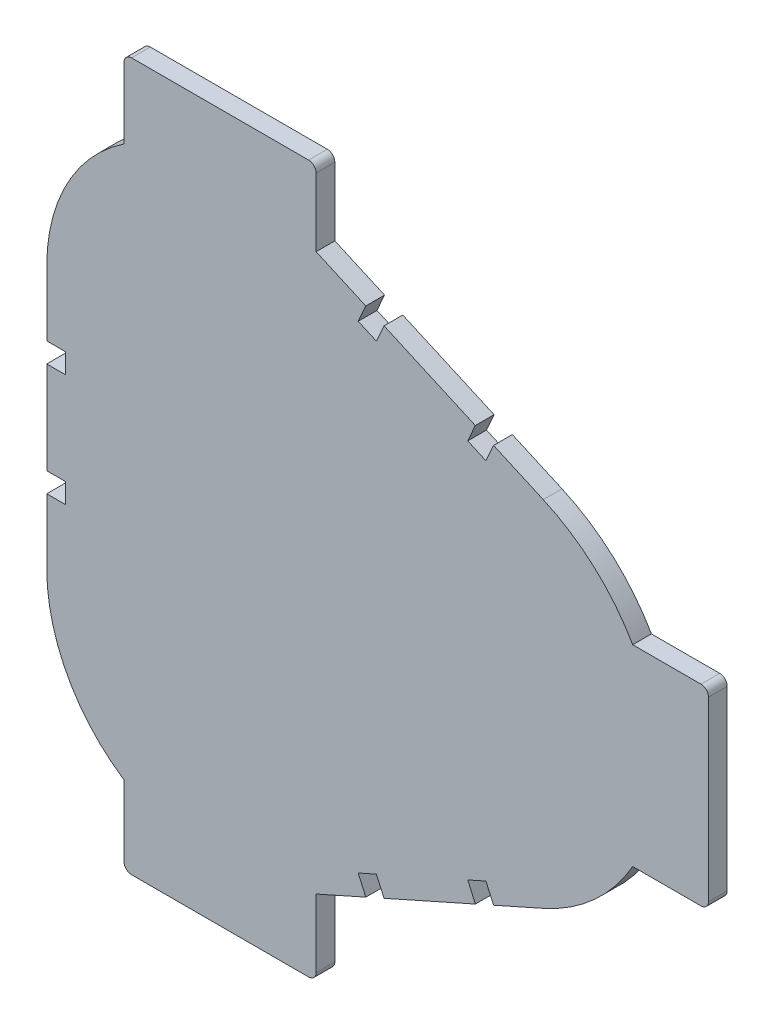
SolidWorks part; units mm, degrees
ref_plane "Front Plane" through (0, 0, 0) normal (0, 0, 1) x (1, 0, 0)
ref_plane "Top Plane" through (0, 0, 0) normal (0, 1, 0) x (1, 0, 0)
ref_plane "Right Plane" through (0, 0, 0) normal (1, 0, 0) x (0, 0, -1)
sketch "Sketch1" plane through (0, 0, -130.81) normal (0, 0, -1) x (-1, 0, 0)
  line L0 (70.5268, 62.4132) -> (70.5268, 49.4592) construction
  line L1 (70.5268, 49.4592) -> (76.8768, 49.4592) construction
  line L2 (76.8768, 49.4592) -> (76.8768, 62.4132) construction
  line L3 (76.8768, 62.4132) -> (70.5268, 62.4132) construction
  line L4 (70.5268, 24.3132) -> (70.5268, 11.3592) construction
  line L5 (70.5268, 11.3592) -> (76.8768, 11.3592) construction
  line L6 (76.8768, 11.3592) -> (76.8768, 24.3132) construction
  line L7 (76.8768, 24.3132) -> (70.5268, 24.3132) construction
  line L8 (76.8768, 52.558) -> (70.5268, 52.558) construction
  line L9 (70.5268, 52.558) -> (70.5268, 21.2144) construction
  line L10 (70.5268, 21.2144) -> (76.8768, 21.2144) construction
  line L11 (76.8768, 21.2144) -> (76.8768, 52.558) construction
  line L12 (-8.0545, -76.637) -> (-8.0545, -54.8958) construction
  line L13 (-9.5612, -52.5755) -> (-28.6575, -44.0718) construction
  line L14 (-28.6575, -44.0718) -> (-31.2406, -49.8726) construction
  line L15 (-31.2406, -49.8726) -> (-14.4045, -57.3699) construction
  line L16 (-14.4045, -57.3699) -> (-14.4045, -80.447) construction
  line L17 (-11.8645, -82.987) -> (48.143, -82.987) construction
  line L18 (50.683, -80.447) -> (50.683, -56.4617) construction
  line L19 (76.8768, -7.5638) -> (76.8768, 14.458) construction
  line L20 (76.8768, 14.458) -> (70.5268, 14.458) construction
  line L21 (70.5268, 14.458) -> (70.5268, -7.5638) construction
  line L22 (44.333, -54.3762) -> (44.333, -76.637) construction
  line L23 (44.333, -76.637) -> (-8.0545, -76.637) construction
  line L24 (-37.6604, -40.0627) -> (-40.2435, -45.8635) construction
  line L25 (-40.2435, -45.8635) -> (-28.4098, -51.1332) construction
  line L26 (-28.4098, -51.1332) -> (-25.8267, -45.3323) construction
  line L27 (-25.8267, -45.3323) -> (-37.6604, -40.0627) construction
  line L28 (-74.7857, -23.5304) -> (-77.3689, -29.3312) construction
  line L29 (-77.3689, -29.3312) -> (-65.5352, -34.6009) construction
  line L30 (-65.5352, -34.6009) -> (-62.952, -28.8001) construction
  line L31 (-62.952, -28.8001) -> (-74.7857, -23.5304) construction
  line L32 (-34.8296, -41.3233) -> (-65.7828, -27.5395) construction
  line L33 (-65.7828, -27.5395) -> (-68.366, -33.3403) construction
  line L34 (-68.366, -33.3403) -> (-37.4127, -47.1241) construction
  line L35 (-37.4127, -47.1241) -> (-34.8296, -41.3233) construction
  line L36 (-121.6907, 69.4299) -> (-144.8373, 69.4299) construction
  line L37 (-147.3773, 66.8899) -> (-147.3773, 6.8824) construction
  line L38 (-144.8373, 4.3424) -> (-121.6907, 4.3424) construction
  line L39 (-91.3743, -23.0945) -> (-74.5381, -30.5918) construction
  line L40 (-74.5381, -30.5918) -> (-71.9549, -24.791) construction
  line L41 (-71.9549, -24.791) -> (-88.7911, -17.2937) construction
  line L42 (-119.4336, 10.6924) -> (-138.4873, 10.6924) construction
  line L43 (-141.0273, 13.2324) -> (-141.0273, 60.5399) construction
  line L44 (-138.4873, 63.0799) -> (-119.4336, 63.0799) construction
  line L45 (-88.7911, 91.066) -> (-71.9549, 98.5633) construction
  line L46 (-71.9549, 98.5633) -> (-74.5381, 104.3642) construction
  line L47 (-74.5381, 104.3642) -> (-91.3743, 96.8669) construction
  line L48 (-74.7857, 97.3027) -> (-62.952, 102.5724) construction
  line L49 (-62.952, 102.5724) -> (-65.5352, 108.3732) construction
  line L50 (-65.5352, 108.3732) -> (-77.3689, 103.1036) construction
  line L51 (-77.3689, 103.1036) -> (-74.7857, 97.3027) construction
  line L52 (-68.366, 107.1127) -> (-65.7828, 101.3118) construction
  line L53 (-65.7828, 101.3118) -> (-34.8296, 115.0956) construction
  line L54 (-34.8296, 115.0956) -> (-37.4127, 120.8965) construction
  line L55 (-37.4127, 120.8965) -> (-68.366, 107.1127) construction
  line L56 (-37.6604, 113.835) -> (-25.8267, 119.1047) construction
  line L57 (-25.8267, 119.1047) -> (-28.4098, 124.9055) construction
  line L58 (-28.4098, 124.9055) -> (-40.2435, 119.6359) construction
  line L59 (-40.2435, 119.6359) -> (-37.6604, 113.835) construction
  line L60 (-28.6575, 117.8441) -> (-9.5612, 126.3479) construction
  line L61 (-8.0545, 128.6682) -> (-8.0545, 147.8693) construction
  line L62 (-5.5145, 150.4093) -> (41.793, 150.4093) construction
  line L63 (44.333, 147.8693) -> (44.333, 128.1486) construction
  line L64 (70.5268, 81.3362) -> (70.5268, 59.3144) construction
  line L65 (70.5268, 59.3144) -> (76.8768, 59.3144) construction
  line L66 (76.8768, 59.3144) -> (76.8768, 81.3362) construction
  line L67 (50.683, 130.234) -> (50.683, 154.2193) construction
  line L68 (48.143, 156.7593) -> (-11.8645, 156.7593) construction
  line L69 (-14.4045, 154.2193) -> (-14.4045, 131.1423) construction
  line L70 (-14.4045, 131.1423) -> (-31.2406, 123.6449) construction
  line L71 (-31.2406, 123.6449) -> (-28.6575, 117.8441) construction
  line L72 (70.5268, 62.4132) -> (70.5268, 49.4592)
  line L73 (70.5268, 49.4592) -> (76.8768, 49.4592)
  line L74 (76.8768, 49.4592) -> (76.8768, 62.4132)
  line L75 (76.8768, 62.4132) -> (70.5268, 62.4132)
  line L76 (70.5268, 24.3132) -> (70.5268, 11.3592)
  line L77 (70.5268, 11.3592) -> (76.8768, 11.3592)
  line L78 (76.8768, 11.3592) -> (76.8768, 24.3132)
  line L79 (76.8768, 24.3132) -> (70.5268, 24.3132)
  line L80 (76.8768, 52.558) -> (70.5268, 52.558)
  line L81 (70.5268, 52.558) -> (70.5268, 21.2144)
  line L82 (70.5268, 21.2144) -> (76.8768, 21.2144)
  line L83 (76.8768, 21.2144) -> (76.8768, 52.558)
  line L84 (-8.0545, -76.637) -> (-8.0545, -54.8958)
  line L85 (-9.5612, -52.5755) -> (-28.6575, -44.0718)
  line L86 (-28.6575, -44.0718) -> (-31.2406, -49.8726)
  line L87 (-31.2406, -49.8726) -> (-14.4045, -57.3699)
  line L88 (-14.4045, -57.3699) -> (-14.4045, -80.447)
  line L89 (-11.8645, -82.987) -> (48.143, -82.987)
  line L90 (50.683, -80.447) -> (50.683, -56.4617)
  line L91 (76.8768, -7.5638) -> (76.8768, 14.458)
  line L92 (76.8768, 14.458) -> (70.5268, 14.458)
  line L93 (70.5268, 14.458) -> (70.5268, -7.5638)
  line L94 (44.333, -54.3762) -> (44.333, -76.637)
  line L95 (44.333, -76.637) -> (-8.0545, -76.637)
  line L96 (-37.6604, -40.0627) -> (-40.2435, -45.8635)
  line L97 (-40.2435, -45.8635) -> (-28.4098, -51.1332)
  line L98 (-28.4098, -51.1332) -> (-25.8267, -45.3323)
  line L99 (-25.8267, -45.3323) -> (-37.6604, -40.0627)
  line L100 (-74.7857, -23.5304) -> (-77.3689, -29.3312)
  line L101 (-77.3689, -29.3312) -> (-65.5352, -34.6009)
  line L102 (-65.5352, -34.6009) -> (-62.952, -28.8001)
  line L103 (-62.952, -28.8001) -> (-74.7857, -23.5304)
  line L104 (-34.8296, -41.3233) -> (-65.7828, -27.5395)
  line L105 (-65.7828, -27.5395) -> (-68.366, -33.3403)
  line L106 (-68.366, -33.3403) -> (-37.4127, -47.1241)
  line L107 (-37.4127, -47.1241) -> (-34.8296, -41.3233)
  line L108 (-121.6907, 69.4299) -> (-144.8373, 69.4299)
  line L109 (-147.3773, 66.8899) -> (-147.3773, 6.8824)
  line L110 (-144.8373, 4.3424) -> (-121.6907, 4.3424)
  line L111 (-91.3743, -23.0945) -> (-74.5381, -30.5918)
  line L112 (-74.5381, -30.5918) -> (-71.9549, -24.791)
  line L113 (-71.9549, -24.791) -> (-88.7911, -17.2937)
  line L114 (-119.4336, 10.6924) -> (-138.4873, 10.6924)
  line L115 (-141.0273, 13.2324) -> (-141.0273, 60.5399)
  line L116 (-138.4873, 63.0799) -> (-119.4336, 63.0799)
  line L117 (-88.7911, 91.066) -> (-71.9549, 98.5633)
  line L118 (-71.9549, 98.5633) -> (-74.5381, 104.3642)
  line L119 (-74.5381, 104.3642) -> (-91.3743, 96.8669)
  line L120 (-74.7857, 97.3027) -> (-62.952, 102.5724)
  line L121 (-62.952, 102.5724) -> (-65.5352, 108.3732)
  line L122 (-65.5352, 108.3732) -> (-77.3689, 103.1036)
  line L123 (-77.3689, 103.1036) -> (-74.7857, 97.3027)
  line L124 (-68.366, 107.1127) -> (-65.7828, 101.3118)
  line L125 (-65.7828, 101.3118) -> (-34.8296, 115.0956)
  line L126 (-34.8296, 115.0956) -> (-37.4127, 120.8965)
  line L127 (-37.4127, 120.8965) -> (-68.366, 107.1127)
  line L128 (-37.6604, 113.835) -> (-25.8267, 119.1047)
  line L129 (-25.8267, 119.1047) -> (-28.4098, 124.9055)
  line L130 (-28.4098, 124.9055) -> (-40.2435, 119.6359)
  line L131 (-40.2435, 119.6359) -> (-37.6604, 113.835)
  line L132 (-28.6575, 117.8441) -> (-9.5612, 126.3479)
  line L133 (-8.0545, 128.6682) -> (-8.0545, 147.8693)
  line L134 (-5.5145, 150.4093) -> (41.793, 150.4093)
  line L135 (44.333, 147.8693) -> (44.333, 128.1486)
  line L136 (70.5268, 81.3362) -> (70.5268, 59.3144)
  line L137 (70.5268, 59.3144) -> (76.8768, 59.3144)
  line L138 (76.8768, 59.3144) -> (76.8768, 81.3362)
  line L139 (50.683, 130.234) -> (50.683, 154.2193)
  line L140 (48.143, 156.7593) -> (-11.8645, 156.7593)
  line L141 (-14.4045, 154.2193) -> (-14.4045, 131.1423)
  line L142 (-14.4045, 131.1423) -> (-31.2406, 123.6449)
  line L143 (-31.2406, 123.6449) -> (-28.6575, 117.8441)
  arc A0 (-8.0545, -54.8958) -> (-9.5612, -52.5755) centre (-10.5945, -54.8958) ccw construction
  arc A1 (-14.4045, -80.447) -> (-11.8645, -82.987) centre (-11.8645, -80.447) ccw construction
  arc A2 (48.143, -82.987) -> (50.683, -80.447) centre (48.143, -80.447) ccw construction
  arc A3 (50.683, -56.4617) -> (76.8768, -7.5638) centre (18.1393, -7.5638) ccw construction
  arc A4 (45.5443, -52.2115) -> (70.5268, -7.5638) centre (18.1393, -7.5638) ccw construction
  arc A5 (45.5443, -52.2115) -> (44.333, -54.3762) centre (46.873, -54.3762) ccw construction
  arc A6 (-144.8373, 69.4299) -> (-147.3773, 66.8899) centre (-144.8373, 66.8899) ccw construction
  arc A7 (-147.3773, 6.8824) -> (-144.8373, 4.3424) centre (-144.8373, 6.8824) ccw construction
  arc A8 (-121.6907, 4.3424) -> (-91.3743, -23.0945) centre (-64.6643, 36.8862) ccw construction
  arc A9 (-117.1843, 9.3325) -> (-88.7911, -17.2937) centre (-64.6643, 36.8862) ccw construction
  arc A10 (-117.1843, 9.3325) -> (-119.4336, 10.6924) centre (-119.4336, 8.1524) ccw construction
  arc A11 (-141.0273, 13.2324) -> (-138.4873, 10.6924) centre (-138.4873, 13.2324) ccw construction
  arc A12 (-138.4873, 63.0799) -> (-141.0273, 60.5399) centre (-138.4873, 60.5399) ccw construction
  arc A13 (-119.4336, 63.0799) -> (-117.1843, 64.4399) centre (-119.4336, 65.6199) ccw construction
  arc A14 (-88.7911, 91.066) -> (-117.1843, 64.4399) centre (-64.6643, 36.8862) ccw construction
  arc A15 (-91.3743, 96.8669) -> (-121.6907, 69.4299) centre (-64.6643, 36.8862) ccw construction
  arc A16 (-9.5612, 126.3479) -> (-8.0545, 128.6682) centre (-10.5945, 128.6682) ccw construction
  arc A17 (-5.5145, 150.4093) -> (-8.0545, 147.8693) centre (-5.5145, 147.8693) ccw construction
  arc A18 (44.333, 147.8693) -> (41.793, 150.4093) centre (41.793, 147.8693) ccw construction
  arc A19 (44.333, 128.1486) -> (45.5443, 125.9839) centre (46.873, 128.1486) ccw construction
  arc A20 (70.5268, 81.3362) -> (45.5443, 125.9839) centre (18.1393, 81.3362) ccw construction
  arc A21 (76.8768, 81.3362) -> (50.683, 130.234) centre (18.1393, 81.3362) ccw construction
  arc A22 (50.683, 154.2193) -> (48.143, 156.7593) centre (48.143, 154.2193) ccw construction
  arc A23 (-11.8645, 156.7593) -> (-14.4045, 154.2193) centre (-11.8645, 154.2193) ccw construction
  arc A24 (-8.0545, -54.8958) -> (-9.5612, -52.5755) centre (-10.5945, -54.8958) ccw
  arc A25 (-14.4045, -80.447) -> (-11.8645, -82.987) centre (-11.8645, -80.447) ccw
  arc A26 (48.143, -82.987) -> (50.683, -80.447) centre (48.143, -80.447) ccw
  arc A27 (50.683, -56.4617) -> (76.8768, -7.5638) centre (18.1393, -7.5638) ccw
  arc A28 (45.5443, -52.2115) -> (70.5268, -7.5638) centre (18.1393, -7.5638) ccw
  arc A29 (45.5443, -52.2115) -> (44.333, -54.3762) centre (46.873, -54.3762) ccw
  arc A30 (-144.8373, 69.4299) -> (-147.3773, 66.8899) centre (-144.8373, 66.8899) ccw
  arc A31 (-147.3773, 6.8824) -> (-144.8373, 4.3424) centre (-144.8373, 6.8824) ccw
  arc A32 (-121.6907, 4.3424) -> (-91.3743, -23.0945) centre (-64.6643, 36.8862) ccw
  arc A33 (-117.1843, 9.3325) -> (-88.7911, -17.2937) centre (-64.6643, 36.8862) ccw
  arc A34 (-117.1843, 9.3325) -> (-119.4336, 10.6924) centre (-119.4336, 8.1524) ccw
  arc A35 (-141.0273, 13.2324) -> (-138.4873, 10.6924) centre (-138.4873, 13.2324) ccw
  arc A36 (-138.4873, 63.0799) -> (-141.0273, 60.5399) centre (-138.4873, 60.5399) ccw
  arc A37 (-119.4336, 63.0799) -> (-117.1843, 64.4399) centre (-119.4336, 65.6199) ccw
  arc A38 (-88.7911, 91.066) -> (-117.1843, 64.4399) centre (-64.6643, 36.8862) ccw
  arc A39 (-91.3743, 96.8669) -> (-121.6907, 69.4299) centre (-64.6643, 36.8862) ccw
  arc A40 (-9.5612, 126.3479) -> (-8.0545, 128.6682) centre (-10.5945, 128.6682) ccw
  arc A41 (-5.5145, 150.4093) -> (-8.0545, 147.8693) centre (-5.5145, 147.8693) ccw
  arc A42 (44.333, 147.8693) -> (41.793, 150.4093) centre (41.793, 147.8693) ccw
  arc A43 (44.333, 128.1486) -> (45.5443, 125.9839) centre (46.873, 128.1486) ccw
  arc A44 (70.5268, 81.3362) -> (45.5443, 125.9839) centre (18.1393, 81.3362) ccw
  arc A45 (76.8768, 81.3362) -> (50.683, 130.234) centre (18.1393, 81.3362) ccw
  arc A46 (50.683, 154.2193) -> (48.143, 156.7593) centre (48.143, 154.2193) ccw
  arc A47 (-11.8645, 156.7593) -> (-14.4045, 154.2193) centre (-11.8645, 154.2193) ccw
  line M24 (-121.6907, 69.4299) -> (-144.8373, 69.4299)
  arc M25 (-144.8373, 69.4299) -> (-147.3773, 66.8899) centre (-144.8373, 66.8899) ccw
  line M26 (-147.3773, 66.8899) -> (-147.3773, 6.8824)
  arc M27 (-147.3773, 6.8824) -> (-144.8373, 4.3424) centre (-144.8373, 6.8824) ccw
  line M28 (-144.8373, 4.3424) -> (-121.6907, 4.3424)
  arc M29 (-121.6907, 4.3424) -> (-91.3743, -23.0945) centre (-64.6643, 36.8862) ccw
  line M30 (-91.3743, -23.0945) -> (-74.5381, -30.5918)
  line M31 (-74.5381, -30.5918) -> (-71.9549, -24.791)
  line M32 (-71.9549, -24.791) -> (-88.7911, -17.2937)
  arc M33 (-88.7911, -17.2937) -> (-117.1843, 9.3325) centre (-64.6643, 36.8862) cw
  arc M34 (-117.1843, 9.3325) -> (-119.4336, 10.6924) centre (-119.4336, 8.1524) ccw
  line M35 (-119.4336, 10.6924) -> (-138.4873, 10.6924)
  arc M36 (-138.4873, 10.6924) -> (-141.0273, 13.2324) centre (-138.4873, 13.2324) cw
  line M37 (-141.0273, 13.2324) -> (-141.0273, 60.5399)
  arc M38 (-141.0273, 60.5399) -> (-138.4873, 63.0799) centre (-138.4873, 60.5399) cw
  line M39 (-138.4873, 63.0799) -> (-119.4336, 63.0799)
  arc M40 (-119.4336, 63.0799) -> (-117.1843, 64.4399) centre (-119.4336, 65.6199) ccw
  arc M41 (-117.1843, 64.4399) -> (-88.7911, 91.066) centre (-64.6643, 36.8862) cw
  line M42 (-88.7911, 91.066) -> (-71.9549, 98.5633)
  line M43 (-71.9549, 98.5633) -> (-74.5381, 104.3642)
  line M44 (-74.5381, 104.3642) -> (-91.3743, 96.8669)
  arc M45 (-91.3743, 96.8669) -> (-121.6907, 69.4299) centre (-64.6643, 36.8862) ccw
extrude "Boss-Extrude1" add sketch "Sketch1" along normal blind 6.35 contours L136 A44 A43 L135 A42 L134 A41 L133 A40 L132 L128 L125 L120 L117 L103 L104 L99 L85 A24 L84 L95 L94 A29 A28 L93 L76 L81 L72 M42 M41 M40 M39 M38 M37 M36 M35 M34 M33 M32 | L72 L137 L74 L75 | L140 A47 L141 L142 L129 L132 A40 L133 A41 L134 A42 L135 A43 A44 L136 L75 L138 A45 L139 A46 | L74 L80 L72 L73 | L79 L83 L73 L81 | L76 L82 L78 L79 | L78 L92 L76 L77 | A28 A29 L94 L95 L84 A24 L85 L98 L87 L88 A25 L89 A26 L90 A27 L91 L77 L93 | L87 L98 L85 L86 | L97 L107 L99 L96 | L102 L106 L96 L104 | L103 L105 L101 L102 | L123 L119 L100 M45 M24 M25 M26 M27 M28 M29 M30 M32 M33 M34 M35 M36 M37 M38 M39 M40 M41 M42 | L100 M32 M30 M31 | L131 L127 L121 L125 | L127 L131 L125 L126 | L130 L143 L128 L129 | L122 L124 L120 L121 | L123 L117 M44 M43
